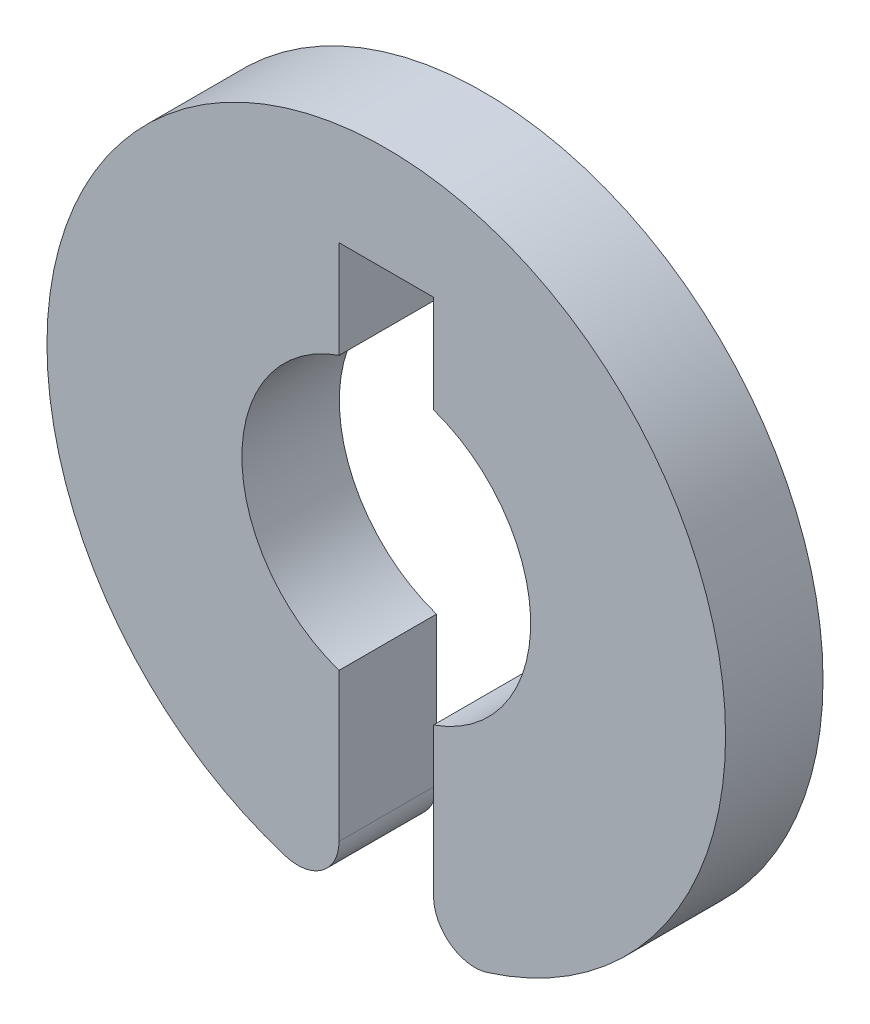
SolidWorks part; units mm, degrees
material "Acrylic (Medium-high impact)"
ref_plane "Front Plane" through (0, 0, 0) normal (0, 0, 1) x (1, 0, 0)
ref_plane "Top Plane" through (0, 0, 0) normal (0, 1, 0) x (1, 0, 0)
ref_plane "Right Plane" through (0, 0, 0) normal (1, 0, 0) x (0, 0, -1)
sketch "스케치1" plane through (0, 0, 0) normal (0, 0, 1) x (1, 0, 0)
  line L0 (0, 10.85) -> (0, 0) construction
  line L6 (-1.4475, 7.2027) -> (1.4475, 7.2027)
  line L7 (0, 0) -> (0, -7.2716) construction
  line L8 (-1.455, -10.3432) -> (1.455, -10.3432) construction
  line L9 (-1.455, -10.3432) -> (-1.455, -4.2001)
  line L10 (-1.455, -4.2001) -> (1.455, -4.2001) construction
  line L11 (1.455, -10.3432) -> (1.455, -4.2001)
  line L12 (-1.455, -10.3432) -> (1.455, -4.2001) construction
  line L13 (-1.455, -4.2001) -> (1.455, -10.3432) construction
  line L14 (-1.4475, 7.2027) -> (-1.4475, 4.2027)
  line L15 (-1.4475, 4.2027) -> (1.4475, 4.2027) construction
  line L16 (1.4475, 7.2027) -> (1.4475, 4.2027)
  line L17 (-1.4475, 7.2027) -> (1.4475, 4.2027) construction
  line L18 (-1.4475, 4.2027) -> (1.4475, 7.2027) construction
  circle A0 centre (0, 0) radius 10.445 construction
  circle A1 centre (0, 0) radius 4.445 construction
  arc A2 (-1.455, -10.3432) -> (1.455, -10.3432) centre (0, 0) cw
  arc A3 (1.455, -4.2001) -> (1.4475, 4.2027) centre (0, 0) ccw
  arc A4 (-1.4475, 4.2027) -> (-1.455, -4.2001) centre (0, 0) ccw
  point P2 (0, 10.85)
  point P5 (0, 5.7027)
  point P10 (0, -7.2716)
  dimension "D1" = 6
  dimension "D2" = 8.89
  dimension "D3" = 2.895
  dimension "D4" = 3
  dimension "D5" = 2.91
extrude "보스-돌출1" add sketch "스케치1" along normal blind 3
fillet "필렛1" radius 1.27 2 edges at (-1.455, -10.3432, 1.5) (1.455, -10.3432, 1.5)
